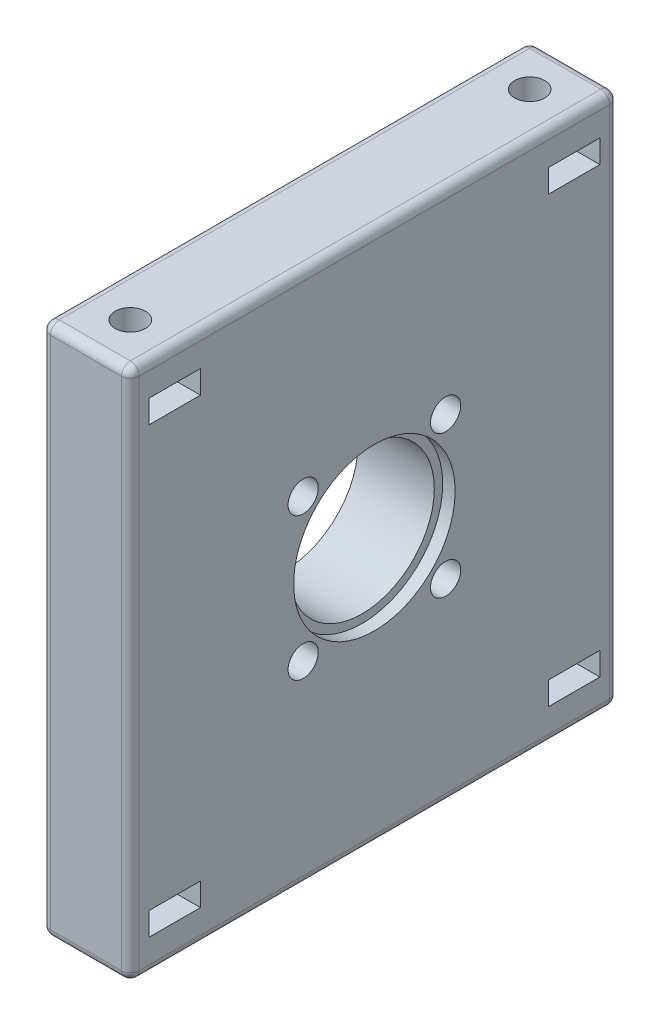
SolidWorks part; units mm, degrees
ref_plane "Front Plane" through (0, 0, 0) normal (0, 0, 1) x (1, 0, 0)
ref_plane "Top Plane" through (0, 0, 0) normal (0, 1, 0) x (1, 0, 0)
ref_plane "Right Plane" through (0, 0, 0) normal (1, 0, 0) x (0, 0, -1)
sketch "Sketch1" plane through (0, 0, 0) normal (1, 0, 0) x (0, 0, -1)
  line L1 (-27.5, 30) -> (27.5, 30)
  line L2 (-27.5, 30) -> (-27.5, -30)
  line L3 (-27.5, -30) -> (27.5, -30)
  line L4 (27.5, 30) -> (27.5, -30)
  line L5 (-27.5, 30) -> (27.5, -30) construction
  line L6 (-27.5, -30) -> (27.5, 30) construction
  point P0 (0, 0)
  dimension "D1" = 55
  dimension "D2" = 60
extrude "Boss-Extrude1" add sketch "Sketch1" along normal blind 10
sketch "Sketch2" plane through (0, 30, 0) normal (0, 1, 0) x (1, 0, 0)
  line L0 (5, 27.5) -> (5, -27.5) construction
  line L1 (10, 27.5) -> (0, 27.5) construction
  line L2 (10, -27.5) -> (0, -27.5) construction
  circle A0 centre (5, 22.5) radius 1.7
  circle A1 centre (5, -22.5) radius 1.7
  dimension "D1" = 3.4
  dimension "D2" = 3.4
  dimension "D3" = 5
  dimension "D4" = 5
extrude "Cut-Extrude1" cut sketch "Sketch2" against normal blind 10
sketch "Sketch3" plane through (0, -30, 0) normal (0, -1, 0) x (1, 0, 0)
  line L0 (5, 27.5) -> (5, -27.5) construction
  line L1 (10, 27.5) -> (0, 27.5) construction
  line L2 (10, -27.5) -> (0, -27.5) construction
  circle A0 centre (5, 22.5) radius 1.7
  circle A1 centre (5, -22.5) radius 1.7
  dimension "D1" = 3.4
  dimension "D2" = 3.4
  dimension "D3" = 5
  dimension "D4" = 5
extrude "Cut-Extrude2" cut sketch "Sketch3" against normal blind 10
sketch "Sketch4" plane through (10, 0, 0) normal (1, 0, 0) x (0, 0, -1)
  line L0 (27.5, 30) -> (-27.5, 30) construction
  line L2 (-25.4, 26.3) -> (-19.6, 26.3)
  line L3 (-25.4, 26.3) -> (-25.4, 23.7)
  line L4 (-25.4, 23.7) -> (-19.6, 23.7)
  line L5 (-19.6, 26.3) -> (-19.6, 23.7)
  line L6 (-25.4, 26.3) -> (-19.6, 23.7) construction
  line L7 (-25.4, 23.7) -> (-19.6, 26.3) construction
  line L8 (19.6, 26.3) -> (25.4, 26.3)
  line L9 (19.6, 26.3) -> (19.6, 23.7)
  line L10 (19.6, 23.7) -> (25.4, 23.7)
  line L11 (25.4, 26.3) -> (25.4, 23.7)
  line L12 (19.6, 26.3) -> (25.4, 23.7) construction
  line L13 (19.6, 23.7) -> (25.4, 26.3) construction
  line L14 (-25.4, -23.7) -> (-19.6, -23.7)
  line L15 (-25.4, -23.7) -> (-25.4, -26.3)
  line L16 (-25.4, -26.3) -> (-19.6, -26.3)
  line L17 (-19.6, -23.7) -> (-19.6, -26.3)
  line L18 (-25.4, -23.7) -> (-19.6, -26.3) construction
  line L19 (-25.4, -26.3) -> (-19.6, -23.7) construction
  line L20 (19.6, -23.7) -> (25.4, -23.7)
  line L21 (19.6, -23.7) -> (19.6, -26.3)
  line L22 (19.6, -26.3) -> (25.4, -26.3)
  line L23 (25.4, -23.7) -> (25.4, -26.3)
  line L24 (19.6, -23.7) -> (25.4, -26.3) construction
  line L25 (19.6, -26.3) -> (25.4, -23.7) construction
  line L26 (-27.5, 30) -> (-27.5, -30) construction
  line L27 (27.5, -30) -> (27.5, 30) construction
  line L28 (-27.5, -30) -> (27.5, -30) construction
  point P0 (-22.5, 25)
  point P5 (22.5, 25)
  point P10 (-22.5, -25)
  point P15 (22.5, -25)
  dimension "D1" = 5.8
  dimension "D2" = 2.6
  dimension "D3" = 5
  dimension "D4" = 5
  dimension "D5" = 5.8
  dimension "D6" = 2.6
  dimension "D7" = 5
  dimension "D8" = 5
  dimension "D9" = 2.6
  dimension "D10" = 5.8
  dimension "D11" = 5
  dimension "D12" = 5
  dimension "D13" = 5.8
  dimension "D14" = 2.6
  dimension "D15" = 5
  dimension "D16" = 5
extrude "Cut-Extrude3" cut sketch "Sketch4" against normal blind 9
sketch "Sketch5" plane through (10, 0, 0) normal (1, 0, 0) x (0, 0, -1)
  line L0 (0, 30) -> (0, -30) construction
  line L1 (27.5, 30) -> (-27.5, 30) construction
  line L2 (-27.5, -30) -> (27.5, -30) construction
  line L3 (-27.5, 0) -> (27.5, 0) construction
  line L4 (-27.5, 30) -> (-27.5, -30) construction
  line L5 (27.5, -30) -> (27.5, 30) construction
  circle A0 centre (0, 0) radius 8.15
  dimension "D1" = 16.3
extrude "Cut-Extrude4" cut sketch "Sketch5" against normal blind 24
sketch "Sketch6" plane through (10, 0, 0) normal (1, 0, 0) x (0, 0, -1)
  circle A0 centre (0, 0) radius 9.1
  dimension "D1" = 18.2
extrude "Cut-Extrude5" cut sketch "Sketch6" against normal blind 1.4
fillet "Fillet1" radius 1 12 edges at (5, -30, -27.5) (0, 0, -27.5) (10, 0, -27.5) (5, 30, -27.5) (0, -30, 0) (10, -30, 0) (0, 30, 0) (10, 30, 0) (5, -30, 27.5) (5, 30, 27.5) (10, 0, 27.5) (0, 0, 27.5)
sketch "Sketch7" plane through (10, 0, 0) normal (1, 0, 0) x (0, 0, -1)
  line L0 (0, 30) -> (0, -30) construction
  line L1 (-26.5, 30) -> (26.5, 30) construction
  line L2 (26.5, -30) -> (-26.5, -30) construction
  line L3 (-27.5, 0) -> (27.5, 0) construction
  line L4 (-27.5, -29) -> (-27.5, 29) construction
  line L5 (27.5, 29) -> (27.5, -29) construction
  line L6 (0, 8.03) -> (8.025, 8.03) construction
  line L7 (0, 8.03) -> (-8.025, 8.03) construction
  line L8 (0, -8.03) -> (8.025, -8.03) construction
  line L9 (0, -8.03) -> (-8.025, -8.03) construction
  circle A0 centre (-8.025, 8.03) radius 1.7
  circle A1 centre (8.025, 8.03) radius 1.7
  circle A2 centre (8.025, -8.03) radius 1.7
  circle A3 centre (-8.025, -8.03) radius 1.7
  dimension "D7" = 3.4
  dimension "D8" = 3.4
  dimension "D9" = 3.4
  dimension "D10" = 3.4
  dimension "D1" = 8.03
  dimension "D2" = 8.03
  dimension "D3" = 8.025
  dimension "D4" = 8.025
  dimension "D5" = 8.025
  dimension "D6" = 8.025
extrude "Cut-Extrude6" cut sketch "Sketch7" against normal blind 27
